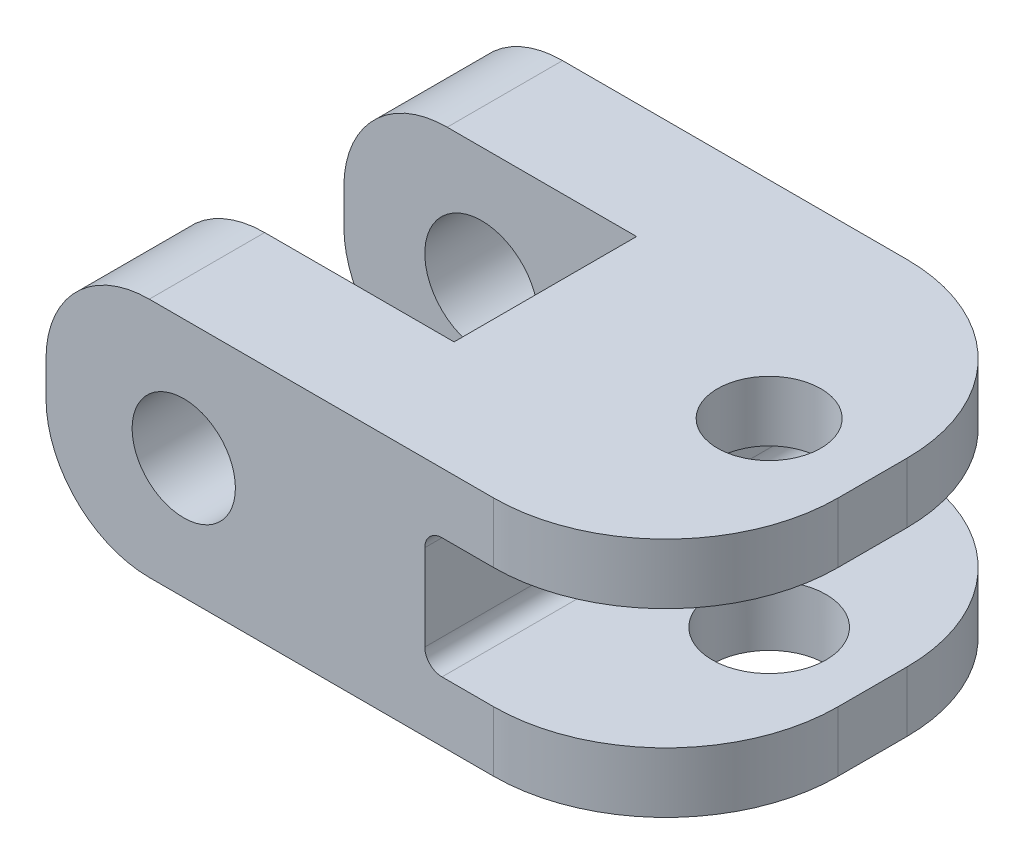
SolidWorks part; units mm, degrees
ref_plane "前视基准面" through (0, 0, 0) normal (0, 0, 1) x (1, 0, 0)
ref_plane "上视基准面" through (0, 0, 0) normal (0, 1, 0) x (1, 0, 0)
ref_plane "右视基准面" through (0, 0, 0) normal (1, 0, 0) x (0, 0, -1)
sketch "草图1" plane through (0, 0, 0) normal (0, 0, 1) x (1, 0, 0)
  line L1 (-9, 3.5) -> (9, 3.5)
  line L2 (-9, 3.5) -> (-9, -3.5)
  line L3 (-9, -3.5) -> (9, -3.5)
  line L4 (9, 3.5) -> (9, -3.5)
  line L5 (-9, 3.5) -> (9, -3.5) construction
  line L6 (-9, -3.5) -> (9, 3.5) construction
  circle A0 centre (-5, 0) radius 1.65
  point P0 (0, 0)
  dimension "D4" = 3.3
  dimension "D1" = 7
  dimension "D2" = 18
  dimension "D3" = 5
extrude "凸台-拉伸1" add sketch "草图1" along normal blind 12
sketch "草图2" plane through (0, 3.5, 0) normal (0, 1, 0) x (1, 0, 0)
  line L0 (-9, -12) -> (-9, 0) construction
  line L1 (-9, -3.35) -> (-0.5, -3.35)
  line L2 (-9, -3.35) -> (-9, -8.65)
  line L3 (-9, -8.65) -> (-0.5, -8.65)
  line L4 (-0.5, -3.35) -> (-0.5, -8.65)
  line L5 (-9, 0) -> (-9, -3.35)
  line L6 (-9, -8.65) -> (-9, -12)
  line M6 (-9, 0) -> (-9, -12)
  dimension "D1" = 5.3
  dimension "D2" = 8.5
extrude "切除-拉伸1" cut sketch "草图2" against normal blind 12 contours L4 L1 L3 M6
sketch "草图3" plane through (0, 0, 12) normal (0, 0, 1) x (1, 0, 0)
  line L0 (9, -3.5) -> (9, 3.5) construction
  line L1 (2, 1.75) -> (16, 1.75)
  line L2 (2, 1.75) -> (2, -1.75)
  line L3 (2, -1.75) -> (16, -1.75)
  line L4 (16, 1.75) -> (16, -1.75)
  line L5 (2, 1.75) -> (16, -1.75) construction
  line L6 (2, -1.75) -> (16, 1.75) construction
  point P0 (9, 0)
  dimension "D1" = 3.5
  dimension "D2" = 7
extrude "切除-拉伸2" cut sketch "草图3" against normal blind 12
sketch "草图4" plane through (0, 3.5, 0) normal (0, 1, 0) x (1, 0, 0)
  line L0 (9, -12) -> (9, 0) construction
  circle A0 centre (6, -6) radius 1.65
  point P4 (9, -6)
  dimension "D2" = 3.3
  dimension "D1" = 3
extrude "切除-拉伸3" cut sketch "草图4" against normal blind 12
fillet "圆角1" radius 5 4 edges at (9, -2.625, 12) (9, 2.625, 12) (9, -2.625, 0) (9, 2.625, 0)
fillet "圆角2" radius 3 4 edges at (-9, -3.5, 10.325) (-9, -3.5, 1.675) (-9, 3.5, 10.325) (-9, 3.5, 1.675)
fillet "圆角3" radius 0.5 2 edges at (2, 1.75, 6) (2, -1.75, 6)
sketch "草图6" plane through (0, 0, 8.65) normal (0, 0, -1) x (-1, 0, 0)
  circle A0 centre (5, 0) radius 1.65 construction
  circle A1 centre (5, 0) radius 1.65
  circle A2 centre (5, 0) radius 1.5
  dimension "D1" = 3
extrude "凸台-拉伸2" add sketch "草图6" against normal up to surface (3.35 mm away) up to face at (-0.5375, 0, 12)
sketch "草图7" plane through (0, 1.75, 0) normal (0, -1, 0) x (1, 0, 0)
  circle A0 centre (6, 6) radius 1.65 construction
  circle A1 centre (6, 6) radius 1.65
  circle A2 centre (6, 6) radius 1.5
  dimension "D1" = 3
extrude "凸台-拉伸3" add sketch "草图7" against normal up to surface (1.75 mm away) up to face at (6, 3.5, 7.65)
